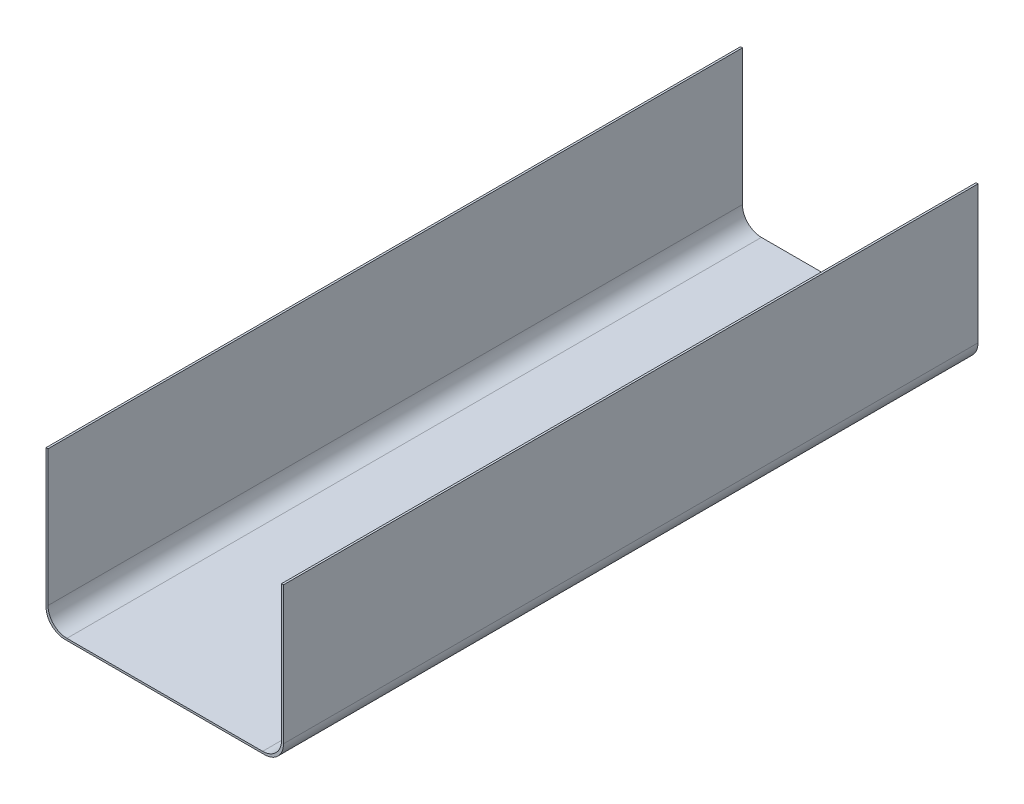
SolidWorks part; units mm, degrees
material "Thornel Mat VMA"
ref_plane "Front Plane" through (0, 0, 0) normal (0, 0, 1) x (1, 0, 0)
ref_plane "Top Plane" through (0, 0, 0) normal (0, 1, 0) x (1, 0, 0)
ref_plane "Right Plane" through (0, 0, 0) normal (1, 0, 0) x (0, 0, -1)
sketch "Sketch1" plane through (0, 0, 0) normal (0, 0, 1) x (1, 0, 0)
  line L1 (46.99, 15.24) -> (47.7838, 15.24)
  line L2 (-46.99, 15.24) -> (-46.99, -39.37)
  line L3 (-39.37, -46.99) -> (39.37, -46.99)
  line L4 (46.99, 15.24) -> (46.99, -39.37)
  line L5 (44.7582, -44.7582) -> (46.99, -46.99) construction
  line L6 (-46.99, -46.99) -> (-44.7582, -44.7582) construction
  line L8 (-47.7837, 15.24) -> (-47.7837, -40.1637)
  line L9 (-40.1637, -47.7837) -> (40.1638, -47.7837)
  line L10 (47.7838, 15.24) -> (47.7838, -40.1637)
  line L11 (44.7582, -44.7582) -> (47.7838, -47.7837) construction
  line L12 (-47.7837, -47.7837) -> (-44.7582, -44.7582) construction
  line L13 (-46.99, 15.24) -> (-47.7837, 15.24)
  arc A0 (-39.37, -46.99) -> (-46.99, -39.37) centre (-39.37, -39.37) cw
  arc A1 (46.99, -39.37) -> (39.37, -46.99) centre (39.37, -39.37) cw
  arc A2 (-40.1637, -47.7837) -> (-47.7837, -40.1637) centre (-40.1637, -40.1637) cw
  arc A3 (47.7838, -40.1637) -> (40.1638, -47.7837) centre (40.1638, -40.1637) cw
  point P0 (0, 0)
  point P12 (0, 0)
extrude "Boss-Extrude1" add sketch "Sketch1" along normal blind 279.4
